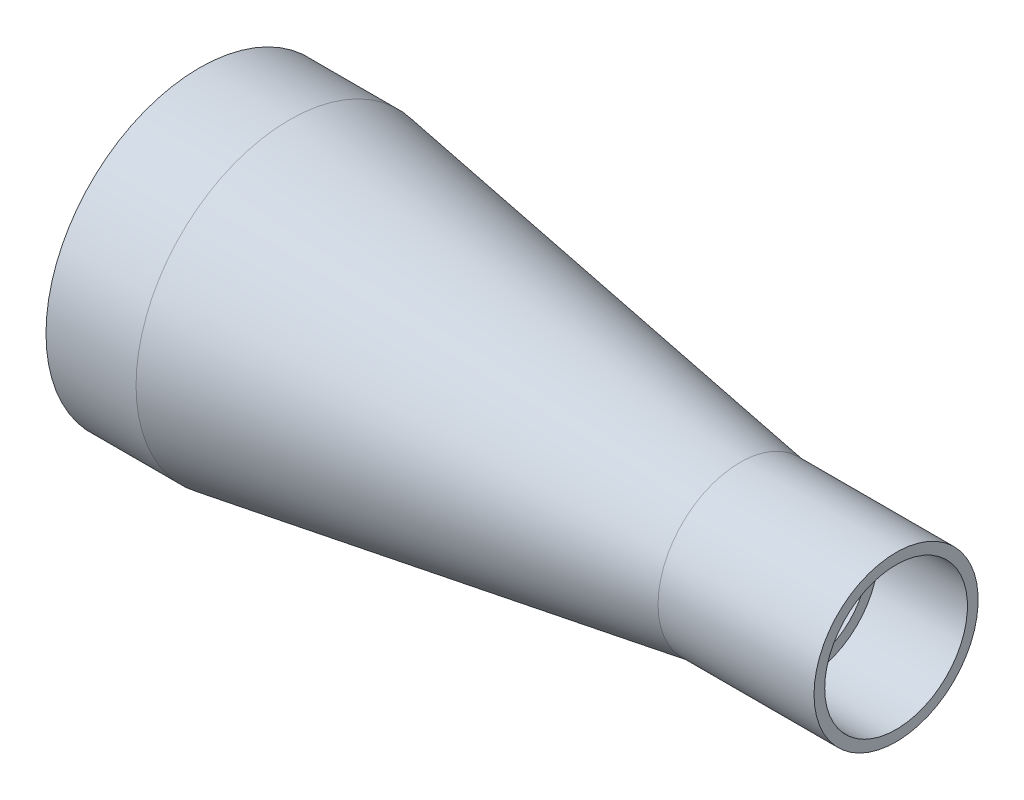
SolidWorks part; units mm, degrees
ref_plane "Front Plane" through (0, 0, 0) normal (0, 0, 1) x (1, 0, 0)
ref_plane "Top Plane" through (0, 0, 0) normal (0, 1, 0) x (1, 0, 0)
ref_plane "Right Plane" through (0, 0, 0) normal (1, 0, 0) x (0, 0, -1)
sketch "Sketch1" plane through (0, 0, 0) normal (0, 1, 0) x (1, 0, 0)
  line L0 (-12.4462, 0) -> (12.9301, 0) construction
  line L1 (0, 10.0134) -> (0, -10.0134) construction
  line L2 (0, 16) -> (-10, 16)
  line L3 (7.5765, 14.8) -> (50.51, 8)
  line L4 (58.0865, 8) -> (68.0865, 8)
  line L5 (50.51, 8) -> (58.0865, 6.8)
  line L6 (58.0865, 6.8) -> (58.0865, 8)
  line L7 (50.6045, 9.2) -> (68.0865, 9.2)
  line L8 (0.0944, 17.2) -> (-10, 17.2)
  line L9 (0.0944, 17.2) -> (50.6045, 9.2)
  line L10 (0.0944, 17.2) -> (50.6977, 9.1852) construction
  line L11 (50.51, 9.2) -> (68.0865, 9.2) construction
  line L12 (-10, 16) -> (-10, 17.2)
  line L13 (68.0865, 8) -> (68.0865, 9.2)
  line L14 (50.51, 8) -> (68.0865, 8) construction
  line L15 (7.5765, 14.8) -> (0, 14.8)
  line L16 (0, 14.8) -> (0, 16)
  line L17 (0, 16) -> (50.51, 8) construction
  point P5 (0, 0)
  dimension "D1" = 10
  dimension "D2" = 10
  dimension "D3" = 9
  dimension "D5" = 1.2
  dimension "D6" = 1.2
  dimension "D7" = 16
  dimension "D8" = 8
  dimension "D4" = 1.2
revolve "Revolve1" add sketch "Sketch1" angle 360 about L0
